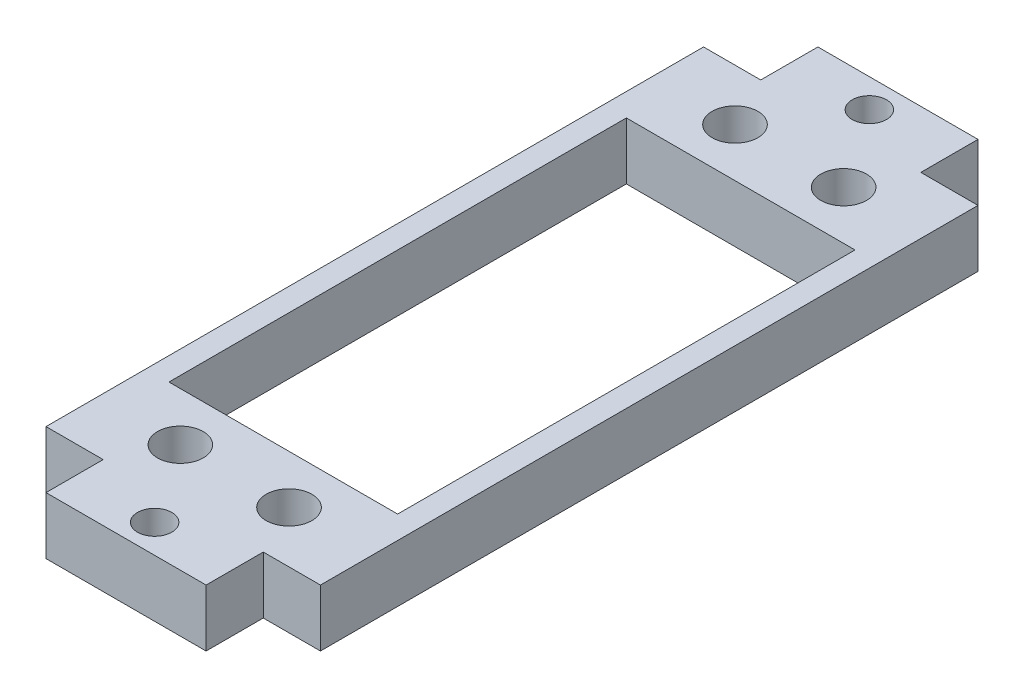
SolidWorks part; units mm, degrees
ref_plane "Front Plane" through (0, 0, 0) normal (0, 0, 1) x (1, 0, 0)
ref_plane "Top Plane" through (0, 0, 0) normal (0, 1, 0) x (1, 0, 0)
ref_plane "Right Plane" through (0, 0, 0) normal (1, 0, 0) x (0, 0, -1)
sketch "Sketch1" plane through (0, 0, 0) normal (0, 1, 0) x (1, 0, 0)
  line L0 (0, 33.75) -> (24, 33.75) construction
  line L1 (5, 0) -> (19, 0)
  line L2 (0, 5) -> (0, 62.5)
  line L3 (5, 67.5) -> (19, 67.5)
  line L4 (24, 5) -> (24, 62.5)
  line L5 (12, 67.5) -> (12, 0) construction
  line L6 (19, 67.5) -> (19, 62.5)
  line L9 (0, 62.5) -> (5, 62.5)
  line L10 (5, 67.5) -> (5, 62.5)
  line L11 (24, 62.5) -> (19, 62.5)
  line L12 (19, 0) -> (19, 5)
  line L13 (24, 5) -> (19, 5)
  line L14 (0, 5) -> (5, 5)
  line L15 (5, 0) -> (5, 5)
  line L16 (5, 62.5) -> (19, 67.5) construction
  line L17 (2, 13.75) -> (22, 13.75)
  line L18 (2, 13.75) -> (2, 53.75)
  line L19 (2, 53.75) -> (22, 53.75)
  line L20 (22, 13.75) -> (22, 53.75)
  line L21 (2, 13.75) -> (22, 53.75) construction
  line L22 (2, 53.75) -> (22, 13.75) construction
  line L23 (12, 58) -> (16.75, 58) construction
  circle A0 centre (12, 65) radius 1.5
  circle A1 centre (12, 2.5) radius 1.5
  circle A2 centre (16.75, 58) radius 2
  circle A3 centre (7.25, 58) radius 2
  circle A4 centre (16.75, 9.5) radius 2
  circle A5 centre (7.25, 9.5) radius 2
  point P0 (12, 33.75)
  point P28 (12, 33.75)
  dimension "D7" = 3
  dimension "D2" = 4
  dimension "D9" = 4.75
  dimension "D1" = 67.5
  dimension "24" = 24
  dimension "D3" = 5
  dimension "D4" = 5
  dimension "D5" = 20
  dimension "D6" = 40
  dimension "D8" = 4.25
extrude "Boss-Extrude1" add sketch "Sketch1" along normal blind 5
